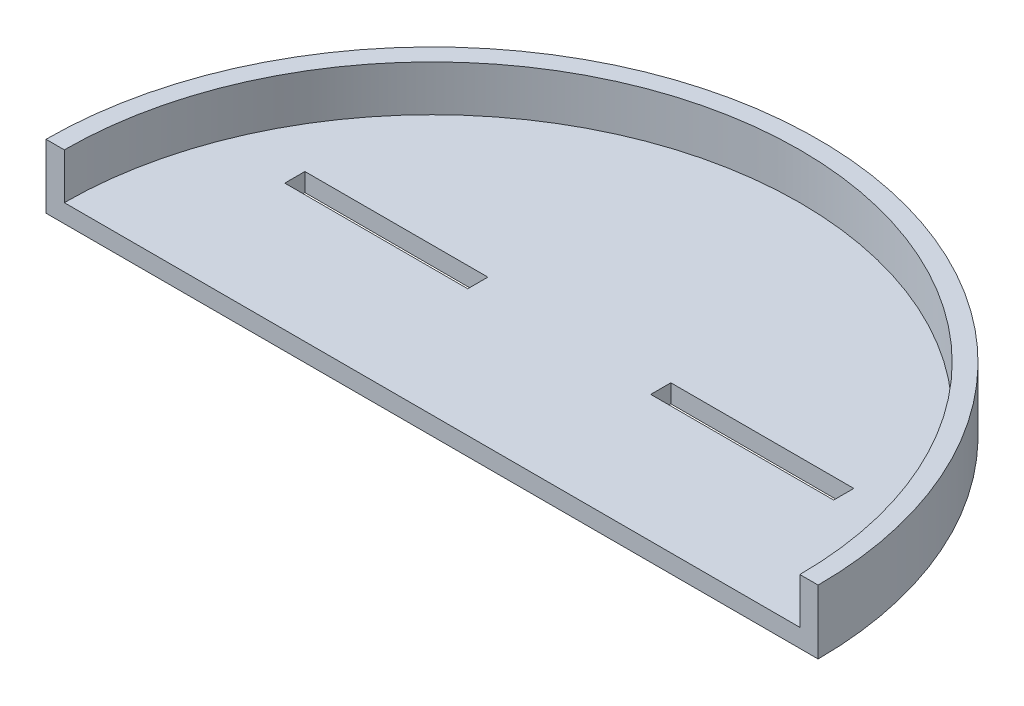
SolidWorks part; units mm, degrees
ref_plane "Front Plane" through (0, 0, 0) normal (0, 0, 1) x (1, 0, 0)
ref_plane "Top Plane" through (0, 0, 0) normal (0, 1, 0) x (1, 0, 0)
ref_plane "Right Plane" through (0, 0, 0) normal (1, 0, 0) x (0, 0, -1)
sketch "Sketch1" plane through (0, 0, 0) normal (0, 1, 0) x (1, 0, 0)
  line L0 (-1.483, 0) -> (-50001.483, 0) construction
  line L1 (0, -2.1496) -> (0, -50002.1496) construction
  circle A0 centre (0, 0) radius 51.054
  circle A1 centre (0, 0) radius 53.594
  dimension "D1" = 102.108
  dimension "D2" = 2.54
extrude "Boss-Extrude2" add sketch "Sketch1" along normal blind 6.35
sketch "Sketch2" plane through (0, 0, 0) normal (0, -1, 0) x (1, 0, 0)
  circle A0 centre (0, 0) radius 53.594
  circle A1 centre (0, 0) radius 53.594 construction
extrude "Boss-Extrude3" add sketch "Sketch2" along normal blind 2.54
sketch "Sketch4" plane through (0, 0, 0) normal (0, 1, 0) x (1, 0, 0)
  line L0 (0, -12.954) -> (0, 51.054) construction
  line L3 (-47.3667, 19.05) -> (47.3667, 19.05) construction
  line L4 (-47.3667, 17.653) -> (47.3667, 17.653)
  line L5 (-47.3667, 20.447) -> (47.3667, 20.447)
  line L6 (38.1, 20.447) -> (38.1, 17.653)
  line L7 (12.7, 20.447) -> (12.7, 17.653)
  line L8 (-12.7, 20.447) -> (-12.7, 17.653)
  line L9 (-38.1, 20.447) -> (-38.1, 17.653)
  circle A0 centre (0, 0) radius 51.054 construction
  circle A1 centre (0, 0) radius 51.054 construction
  point P7 (0, 19.05)
  point P18 (0, 19.05)
  point P25 (12.7, 19.05)
  point P26 (0, 0)
  point P33 (0, 0)
  point P34 (0, 0)
  point P35 (0, 0)
  dimension "D3" = 1.397
  dimension "D5" = 12.7
  dimension "D6" = 25.4
  dimension "D7" = 19.05
  dimension "D4" = 1.397
extrude "Cut-Extrude1" cut sketch "Sketch4" against normal through all contours L5 L9 L4 L8 | L5 L7 L4 L6
sketch "Sketch5" plane through (0, -2.54, 0) normal (0, -1, 0) x (1, 0, 0)
  line L0 (-69.85, 0) -> (69.85, 0)
  circle A1 centre (0, 0) radius 69.85
  circle M2 centre (0, 0) radius 53.594
  dimension "D1" = 139.7
  dimension "D2" = 0
extrude "Cut-Extrude2" cut sketch "Sketch5" against normal through all contours L0 A1 M2 | L0 M2
